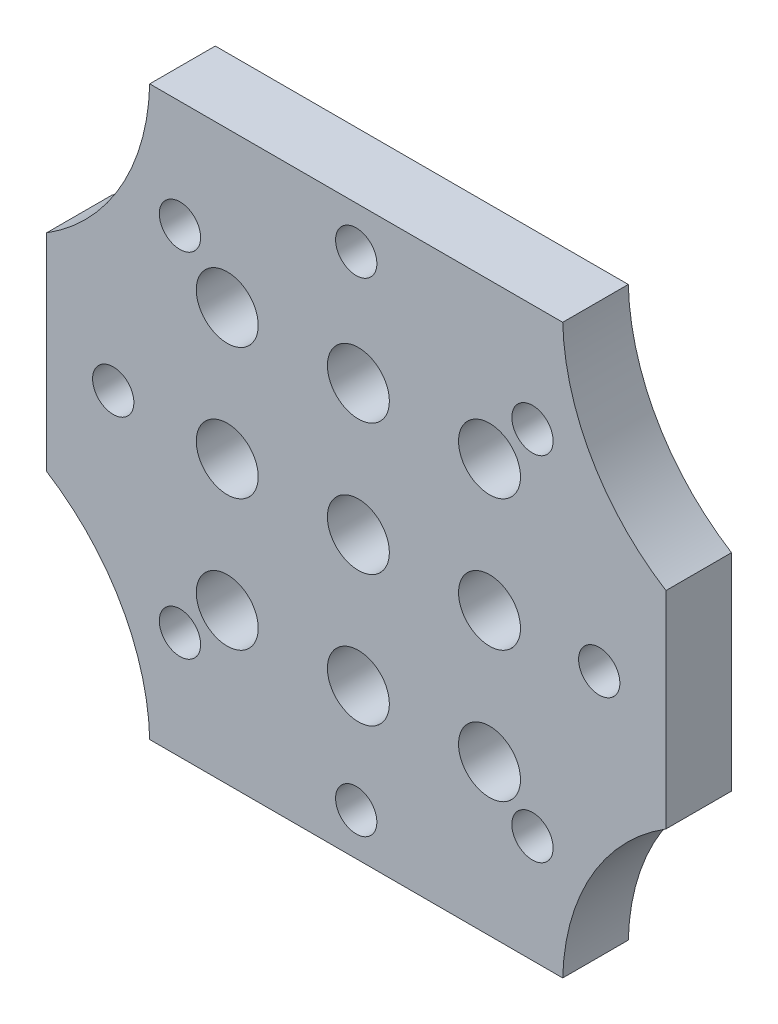
SolidWorks part; units mm, degrees
material "Custom Plastic"
ref_plane "X-Y Datum" through (0, 0, 0) normal (0, 0, 1) x (1, 0, 0)
ref_plane "X-Z Datum" through (0, 0, 0) normal (0, 1, 0) x (1, 0, 0)
ref_plane "Y-Z Datum" through (0, 0, 0) normal (1, 0, 0) x (0, 0, -1)
sketch "Sketch1" plane through (0, 0, 0) normal (0, 0, 1) x (1, 0, 0)
  line L1 (-30, -27.5) -> (30, -27.5)
  line L2 (-30, -27.5) -> (-30, 27.5)
  line L3 (-30, 27.5) -> (30, 27.5)
  line L4 (30, -27.5) -> (30, 27.5)
  line L5 (-30, -27.5) -> (30, 27.5) construction
  line L6 (-30, 27.5) -> (30, -27.5) construction
  point P0 (0, 0)
  dimension "D1" = 60
  dimension "D2" = 55
extrude "Boss-Extrude1" add sketch "Sketch1" along normal blind 6.35
sketch "Sketch2" plane through (0, 0, 6.35) normal (0, 0, 1) x (1, 0, 0)
  line L0 (-30, 0) -> (-17.0711, 0) construction
  line L1 (-17.0711, -17.0711) -> (17.0711, -17.0711) construction
  line L2 (-17.0711, -17.0711) -> (-17.0711, 17.0711) construction
  line L3 (-17.0711, 17.0711) -> (17.0711, 17.0711) construction
  line L4 (17.0711, -17.0711) -> (17.0711, 17.0711) construction
  line L5 (-17.0711, -17.0711) -> (17.0711, 17.0711) construction
  line L6 (-17.0711, 17.0711) -> (17.0711, -17.0711) construction
  line L7 (-30, 27.5) -> (-30, -27.5) construction
  line L8 (17.0711, 0) -> (30, 0) construction
  line L9 (30, -27.5) -> (30, 27.5) construction
  line L10 (-30, 0) -> (-30, 10) construction
  line L11 (0, 17.0711) -> (0, 27.5) construction
  line L12 (30, 27.5) -> (-30, 27.5) construction
  line L13 (0, 27.5) -> (-20, 27.5) construction
  line L15 (0, -43.0151) -> (0, 43.0151) construction
  line L16 (55.1739, 0) -> (-55.1739, 0) construction
  circle A0 centre (-17.0711, 17.0711) radius 2
  circle A1 centre (17.0711, 17.0711) radius 2
  circle A2 centre (-17.0711, -17.0711) radius 2
  circle A3 centre (17.0711, -17.0711) radius 2
  circle A4 centre (-23.5355, 0) radius 2
  circle A5 centre (23.5355, 0) radius 2
  arc A6 (-30, 10) -> (-20, 27.5) centre (-41.2994, 28.0639) ccw
  arc A7 (30, 10) -> (20, 27.5) centre (41.2994, 28.0639) cw
  arc A8 (-30, -10) -> (-20, -27.5) centre (-41.2994, -28.0639) cw
  arc A9 (30, -10) -> (20, -27.5) centre (41.2994, -28.0639) ccw
  circle A10 centre (0, 23.4211) radius 2
  circle A11 centre (0, -23.4211) radius 2
  point P0 (0, 0)
  line M3 (30, -27.5) -> (30, 27.5)
  line M4 (30, 27.5) -> (-30, 27.5)
  line M5 (-30, 27.5) -> (-30, -27.5)
  line M6 (-30, -27.5) -> (30, -27.5)
  dimension "D1" = 4
  dimension "D2" = 4
  dimension "D5" = 6.35
  dimension "D3" = 10
  dimension "D4" = 20
  dimension "D6" = 6.35
extrude "Cut-Extrude1" cut sketch "Sketch2" against normal blind 6.35 contours A6 M5 M4 | A8 M5 M6 | A9 M3 M6 | A7 M3 M4 | A1 | A5 | A3 | A2 | A4 | A0 | A11 | A10
sketch "Sketch3" plane through (0, 0, 6.35) normal (0, 0, 1) x (1, 0, 0)
  line L0 (-17.0711, 17.0711) -> (17.0711, -17.0711) construction
  circle A0 centre (-12.4909, 12.4909) radius 3
extrude "Cut-Extrude2" cut sketch "Sketch3" against normal through all
pattern_linear "LPattern1" count 3 spacing 12.7 along (1, 0, 0) of "Cut-Extrude2"
pattern_linear "LPattern2" count 3 spacing 12.7 along (0, -1, 0) of "LPattern1", "Cut-Extrude2"
